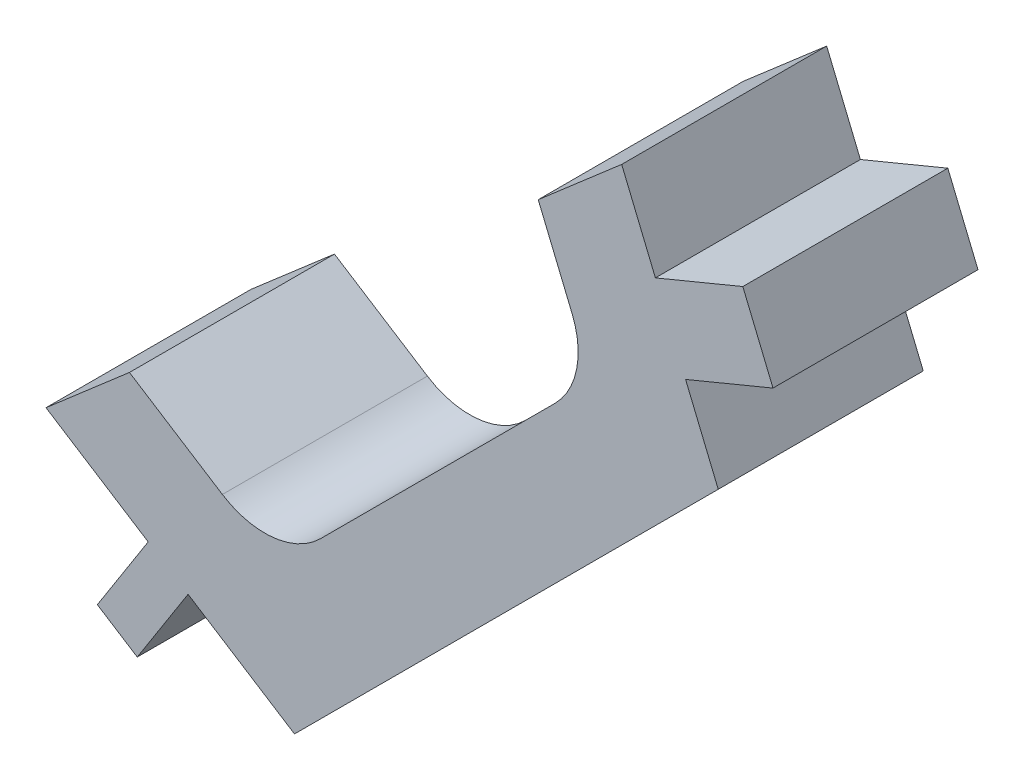
SolidWorks part; units mm, degrees
ref_plane "Plane1" through (0, 0, 0) normal (0, 0, 1) x (1, 0, 0)
ref_plane "Plane2" through (0, 0, 0) normal (0, 1, 0) x (1, 0, 0)
ref_plane "Plane3" through (0, 0, 0) normal (1, 0, 0) x (0, 0, -1)
sketch "Sketch1" plane through (0, 0, 0) normal (0, 0, 1) x (1, 0, 0)
  line L1 (0, 0) -> (203.2, 0)
  line L2 (0, 0) -> (0, 101.6)
  line L3 (0, 101.6) -> (203.2, 101.6)
  line L4 (203.2, 0) -> (203.2, 101.6)
  dimension "D1" = 203.2
  dimension "D2" = 101.6
extrude "Extrude1" add sketch "Sketch1" along normal blind 50.8
sketch "Sketch2" plane through (0, 0, 50.8) normal (0, 0, 1) x (1, 0, 0)
  line L0 (83.0232, 99.06) -> (89.3732, 99.06)
  line L2 (157.48, 83.82) -> (157.48, 78.74)
  line L3 (157.48, 78.74) -> (91.44, 78.74)
  line L4 (91.44, 78.74) -> (83.0232, 99.06)
  line L5 (203.2, 101.6) -> (0, 101.6) construction
  line L6 (0, 101.6) -> (0, 0) construction
  line L7 (157.48, 83.82) -> (102.4931, 88.7077)
  line L8 (98.7377, 90.3765) -> (89.3732, 99.06)
  arc A0 (98.7377, 90.3765) -> (102.4931, 88.7077) centre (103.0553, 95.0328) ccw
  point P12 (100.33, 88.9)
  dimension "D10" = 6.35
  dimension "D1" = 67.5
  dimension "D2" = 20.32
  dimension "D3" = 2.54
  dimension "D4" = 5.08
  dimension "D5" = 66.04
  dimension "D6" = 157.48
  dimension "D7" = 6.35
  dimension "D8" = 57.15
  dimension "D9" = 5.08
sketch "Sketch4" plane through (0, 0, 50.8) normal (0, 0, 1) x (1, 0, 0)
  line L0 (86.5799, 90.4733) -> (72.5, 84.6412)
  line L1 (91.44, 78.74) -> (83.0232, 99.06) construction
  line L2 (72.5, 84.6412) -> (69.6673, 84.8425)
  line L3 (69.6673, 84.8425) -> (73.0694, 76.6292)
  line L4 (73.0694, 76.6292) -> (74.93, 78.7745)
  line L5 (74.93, 78.7745) -> (89.01, 84.6066)
  line L6 (89.01, 84.6066) -> (91.8426, 84.4053)
  line L7 (91.8426, 84.4053) -> (88.4406, 92.6186)
  line L8 (88.4406, 92.6186) -> (86.5799, 90.4733)
  line L9 (79.54, 87.5572) -> (81.97, 81.6906)
  dimension "D1" = 6.35
  dimension "D2" = 8.89
  dimension "D3" = 1.27
  dimension "D4" = 8.89
  dimension "D5" = 1.27
  dimension "D6" = 2.54
  dimension "D7" = 2.54
  dimension "D8" = 15.24
  dimension "D9" = 6.35
sketch "Sketch5" plane through (0, 0, 50.8) normal (0, 0, 1) x (1, 0, 0)
  line L0 (69.7842, 91.1978) -> (77.5603, 72.4245)
  line L1 (77.5603, 72.4245) -> (43.4353, 38.2996)
  line L2 (43.4353, 38.2996) -> (23.4233, 51.0486)
  line L5 (23.4233, 51.0486) -> (30.1436, 56.8684)
  line L6 (157.48, 78.74) -> (91.44, 78.74) construction
  line L7 (30.1436, 56.8684) -> (37.6275, 52.1007)
  line L8 (45.5295, 52.9661) -> (64.4212, 71.8578)
  line L9 (65.7977, 78.778) -> (63.0639, 85.3779)
  line L10 (63.0639, 85.3779) -> (69.7842, 91.1978)
  arc A0 (37.6275, 52.1007) -> (45.5295, 52.9661) centre (41.0393, 57.4562) ccw
  arc A1 (65.7977, 78.778) -> (64.4212, 71.8578) centre (59.9311, 76.3479) cw
  point P14 (41.9258, 49.3624)
  dimension "D10" = 6.35
  dimension "D1" = 135
  dimension "D2" = 6.35
  dimension "D3" = 8.89
  dimension "D4" = 48.26
  dimension "D5" = 102.5
  dimension "D6" = 8.89
  dimension "D7" = 20.32
  dimension "D8" = 8.89
  dimension "D9" = 13.97
sketch "Sketch6" plane through (0, 0, 50.8) normal (0, 0, 1) x (1, 0, 0)
  line L0 (31.6531, 45.8056) -> (23.4647, 32.9524)
  line L1 (43.4353, 38.2996) -> (23.4233, 51.0486) construction
  line L2 (23.4647, 32.9524) -> (21.0288, 31.4925)
  line L3 (21.0288, 31.4925) -> (26.3844, 28.0807)
  line L4 (26.3844, 28.0807) -> (26.678, 30.9052)
  line L5 (26.678, 30.9052) -> (34.8665, 43.7585)
  line L6 (34.8665, 43.7585) -> (37.3023, 45.2184)
  line L7 (37.3023, 45.2184) -> (31.9468, 48.6302)
  line L8 (30.7722, 37.3319) -> (27.5589, 39.379)
  line L9 (31.9468, 48.6302) -> (31.6531, 45.8056)
  line L10 (27.5589, 39.379) -> (30.7722, 37.3319)
  line L11 (34.8665, 43.7585) -> (43.4353, 38.2996)
  line L12 (43.4353, 38.2996) -> (77.5603, 72.4245)
  line L13 (77.5603, 72.4245) -> (74.93, 78.7745)
  line L14 (74.93, 78.7745) -> (81.97, 81.6906)
  line L15 (81.97, 81.6906) -> (79.54, 87.5572)
  line L16 (79.54, 87.5572) -> (72.5, 84.6412)
  line L17 (72.5, 84.6412) -> (69.7842, 91.1978)
  line L18 (69.7842, 91.1978) -> (63.0639, 85.3779)
  line L19 (63.0639, 85.3779) -> (65.7977, 78.778)
  line L20 (64.4212, 71.8578) -> (45.5295, 52.9661)
  line L21 (37.6275, 52.1007) -> (30.1436, 56.8684)
  line L22 (30.1436, 56.8684) -> (23.4233, 51.0486)
  line L23 (23.4233, 51.0486) -> (31.6531, 45.8056)
  arc A0 (65.7977, 78.778) -> (64.4212, 71.8578) centre (59.9311, 76.3479) cw
  arc A2 (37.6275, 52.1007) -> (45.5295, 52.9661) centre (41.0393, 57.4562) ccw
  dimension "D1" = 3.81
  dimension "D2" = 6.35
  dimension "D3" = 6.35
  dimension "D4" = 1.27
  dimension "D5" = 1.27
  dimension "D6" = 2.54
  dimension "D7" = 2.54
  dimension "D8" = 15.24
  dimension "D9" = 10.16
sketch "Sketch8" plane through (0, 0, 50.8) normal (0, 0, 1) x (1, 0, 0)
  line L0 (16.648, 37.2951) -> (33.1047, 26.811)
  line L1 (33.1047, 26.811) -> (26.5892, 8.9099)
  line L2 (26.5892, 8.9099) -> (2.721, 17.5972)
  line L3 (16.648, 37.2951) -> (10.6809, 39.4669)
  line L4 (2.721, 17.5972) -> (10.6809, 39.4669)
  line L8 (43.4353, 38.2996) -> (23.4233, 51.0486) construction
  dimension "D1" = 7.62
  dimension "D2" = 102.5
  dimension "D3" = 25.4
  dimension "D4" = 19.05
  dimension "D5" = 6.35
sketch "Sketch14" plane through (0, 0, 50.8) normal (0, 0, 1) x (1, 0, 0)
  line L0 (157.48, 78.74) -> (91.44, 78.74) construction
  line L1 (93.98, 80.772) -> (154.94, 80.772)
  line L2 (93.98, 80.772) -> (93.98, 74.422)
  line L3 (93.98, 74.422) -> (154.94, 74.422)
  line L4 (154.94, 80.772) -> (154.94, 74.422)
  line L5 (157.48, 83.82) -> (157.48, 78.74) construction
  dimension "D1" = 2.032
  dimension "D2" = 2.54
  dimension "D3" = 2.54
  dimension "D4" = 6.35
sketch "Sketch15" plane through (0, 0, 50.8) normal (0, 0, 1) x (1, 0, 0)
  line L0 (43.7945, 41.5325) -> (48.2847, 37.0423)
  line L2 (48.2847, 37.0423) -> (78.8175, 67.5752)
  line L3 (78.8175, 67.5752) -> (74.3274, 72.0653)
  line L4 (74.3274, 72.0653) -> (43.7945, 41.5325)
  line L5 (77.5603, 72.4245) -> (43.4353, 38.2996) construction
  dimension "D1" = 2.032
  dimension "D2" = 2.54
  dimension "D3" = 6.35
  dimension "D4" = 2.54
sketch "Sketch16" plane through (0, 0, 50.8) normal (0, 0, 1) x (1, 0, 0)
  line L0 (25.5485, 11.9917) -> (31.5155, 9.8199)
  line L1 (31.5155, 9.8199) -> (36.2935, 22.9474)
  line L2 (36.2935, 22.9474) -> (30.3265, 25.1192)
  line L3 (30.3265, 25.1192) -> (25.5485, 11.9917)
  line L4 (33.1047, 26.811) -> (26.5892, 8.9099) construction
  dimension "D1" = 2.032
  dimension "D2" = 6.35
  dimension "D3" = 2.54
  dimension "D4" = 2.54
sketch "Sketch19" plane through (0, 0, 50.8) normal (0, 0, 1) x (1, 0, 0)
  line L0 (155.194, 72.39) -> (86.506, 72.39)
  line L1 (86.506, 72.39) -> (45.2314, 31.1154)
  line L2 (45.2314, 31.1154) -> (113.9194, 31.1154)
  line L3 (113.9194, 31.1154) -> (155.194, 72.39)
  line L4 (93.98, 74.422) -> (154.94, 74.422) construction
  line L5 (48.2847, 37.0423) -> (78.8175, 67.5752) construction
  line L7 (43.7945, 41.5325) -> (48.2847, 37.0423) construction
  line L8 (154.94, 80.772) -> (154.94, 74.422) construction
  dimension "D1" = 2.032
  dimension "D2" = 2.032
  dimension "D3" = 6.35
  dimension "D4" = 0.254
extrude "Extrude2" add sketch "Sketch6" along normal blind 16.51 contours A2 L21 L22 L23 L9 L7 L6 L11 L12 L13 L14 L15 L16 L17 L18 L19 A0 L20 | L7 L9 L0 L8 L5 L6
sketch "Sketch20" plane through (0, 0, 0) normal (0, -1, 0) x (1, 0, 0)
  line L0 (0, 2.8216) -> (0, 50.8)
  line L1 (0, 50.8) -> (0, 0) construction
  line L2 (0, 50.8) -> (203.2, 50.8)
  line L3 (203.2, 50.8) -> (203.2, 0)
  line L4 (203.2, 0) -> (0, 0)
  line L5 (0, 0) -> (0, 50.8)
  line M1 (0, 0) -> (203.2, 0)
  line M2 (203.2, 0) -> (203.2, 50.8)
  line M3 (203.2, 50.8) -> (0, 50.8)
  line M4 (0, 50.8) -> (0, 0)
extrude "Extrude3" cut sketch "Sketch20" against normal blind 1270 contours M4 M1 M2 M3
sketch "Sketch21" plane through (25.8008, 40.4991, 0) normal (-0.5373, -0.8434, 0) x (0.8434, -0.5373, 0)
  line L0 (5.8946, 67.31) -> (5.8946, 50.8) construction
  point P0 (5.8946, 59.055)
